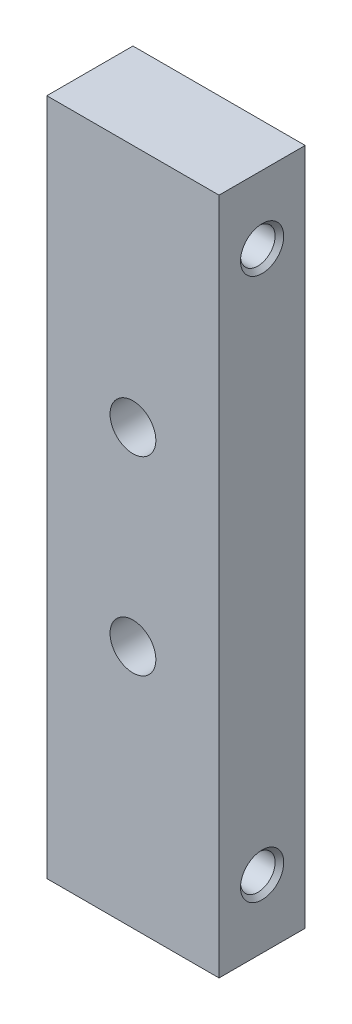
SolidWorks part; units mm, degrees
ref_plane "Alzado" through (0, 0, 0) normal (0, 0, 1) x (1, 0, 0)
ref_plane "Planta" through (0, 0, 0) normal (0, 1, 0) x (1, 0, 0)
ref_plane "Vista lateral" through (0, 0, 0) normal (1, 0, 0) x (0, 0, -1)
sketch "Croquis1" plane through (0, 0, 0) normal (0, 0, 1) x (1, 0, 0)
  line L0 (0, 0) -> (50000, 0) construction
  line L1 (-12.7, 50) -> (12.7, 50)
  line L2 (-12.7, 50) -> (-12.7, -50)
  line L3 (-12.7, -50) -> (12.7, -50)
  line L4 (12.7, 50) -> (12.7, -50)
  circle A0 centre (0, 30) radius 6 construction
  circle A1 centre (0, -30) radius 6 construction
  point P4 (0, 50)
  point P5 (-12.7, 0)
  dimension "D3" = 12
  dimension "D1" = 100
  dimension "D2" = 25.4
  dimension "D4" = 20
extrude "Saliente-Extruir1" add sketch "Croquis1" along normal mid plane 12.7
hole_wizard "Taladro de margen para 1/41" positions "Croquis2" profile "Croquis3" hole size "1/4" standard "Ansi Inch" end condition through all
sketch "Croquis2" plane through (-6.35, 0, 6.35) normal (0, 0, -1) x (-1, 0, 0)
  line L1 (-4.3432, 0) -> (-3.4478, 0) construction
  point P0 (-6.35, -14)
  point P3 (-6.35, 14)
  point P16 (0, 0)
  point P17 (0, 0)
  point P18 (0, 0)
  point P19 (0, 0)
  dimension "D1" = 14
sketch "Croquis3" plane through (0, -14, 6.35) normal (1, 0, 0) x (0, -1, 0)
  line L0 (0, 0) -> (0, 12.7)
  line L1 (0, 12.7) -> (3.3782, 12.7)
  line L2 (3.3782, 12.7) -> (3.3782, 0)
  line L5 (3.3782, 0) -> (0, 0)
  line L11 (0, -6.35) -> (0, 107.95) construction
  dimension "Diámetro de taladro hasta el siguiente" = 6.7564
  dimension "Profundidad de taladro hasta el siguiente" = 12.7
hole_wizard "Taladro roscado 1/4-202" positions "Croquis6" profile "Croquis7" tap size "1/4-20" standard "Ansi Inch" end condition through all
sketch "Croquis6" plane through (-12.7, 0, 0) normal (-1, 0, 0) x (0, 0, 1)
  line L0 (0, 0) -> (50000, 0) construction
  line L2 (6.35, 50) -> (-6.35, 50) construction
  point P0 (0, 40)
  point P2 (0, -40)
  point P10 (0, 40.0929)
  dimension "D1" = 10
sketch "Croquis7" plane through (-12.7, 40, 0) normal (0, 1, 0) x (0, 0, 1)
  line L0 (0, 0) -> (0, 25.4)
  line L1 (0, 25.4) -> (3.1877, 25.4)
  line L2 (2.5527, 24.765) -> (2.5527, 0.635)
  line L3 (2.5527, 0.635) -> (3.1877, 0)
  line L5 (3.1877, 0) -> (0, 0)
  line L6 (-2.5527, 0.635) -> (-3.1877, 0) construction
  line L7 (3.1877, 25.4) -> (2.5527, 24.765)
  line L8 (-3.1877, 25.4) -> (-2.5527, 24.765) construction
  line L11 (0, -6.35) -> (0, 107.95) construction
  dimension "Diámetro de perforador para roscar hasta el siguiente" = 5.1054
  dimension "Profundidad de perforador para roscar hasta el siguiente" = 25.4
  dimension "Diámetro de avellanado cercano" = 6.3754
  dimension "Ángulo de avellanado cercano" = 90
  dimension "Diámetro de avellanado lejano" = 6.3754
  dimension "Ángulo de avellanado lejano" = 90
cosmetic thread "Rosca de taladro7"
cosmetic thread "Rosca de taladro8"
hole_wizard "Taladro roscado 3/8-161" [suppressed] positions "Croquis4" profile "Croquis5" tap size "3/8-16" standard "Ansi Inch"
sketch "Croquis4" plane through (0, 0, 6.35) normal (0, 0, 1) x (1, 0, 0)
  point P0 (0, 0)
sketch "Croquis5" plane through (0, 0, 6.35) normal (1, 0, 0) x (0, -1, 0)
  line L0 (0, 0) -> (0, 12.7)
  line L1 (0, 12.7) -> (5.3975, 12.7)
  line L2 (3.9687, 11.2712) -> (3.9687, 1.4287)
  line L3 (3.9687, 1.4287) -> (5.3975, 0)
  line L5 (5.3975, 0) -> (0, 0)
  line L6 (-3.9687, 1.4287) -> (-5.3975, 0) construction
  line L7 (5.3975, 12.7) -> (3.9687, 11.2712)
  line L8 (-5.3975, 12.7) -> (-3.9688, 11.2712) construction
  line L11 (0, -6.35) -> (0, 107.95) construction
  dimension "Diámetro de perforador para roscar hasta el siguiente" = 7.9375
  dimension "Profundidad de perforador para roscar hasta el siguiente" = 12.7
  dimension "Diámetro de avellanado cercano" = 10.795
  dimension "Ángulo de avellanado cercano" = 90
  dimension "Diámetro de avellanado lejano" = 10.795
  dimension "Ángulo de avellanado lejano" = 90
cosmetic thread "Rosca de taladro6" [suppressed] parameters "D2"=9.525
hole_wizard "Taladro de margen para M101" [suppressed] positions "Croquis8" profile "Croquis9" hole size "M10" standard "Ansi Metric"
sketch "Croquis8" plane through (0, 0, 6.35) normal (0, 0, 1) x (1, 0, 0)
  point P0 (0, 0)
sketch "Croquis9" plane through (0, 0, 6.35) normal (1, 0, 0) x (0, -1, 0)
  line L0 (0, 0) -> (0, 12.7)
  line L1 (0, 12.7) -> (5.5, 12.7)
  line L2 (5.5, 12.7) -> (5.5, 0)
  line L5 (5.5, 0) -> (0, 0)
  line L11 (0, -6.35) -> (0, 107.95) construction
  dimension "Diámetro de taladro hasta el siguiente" = 11
  dimension "Profundidad de taladro hasta el siguiente" = 12.7
